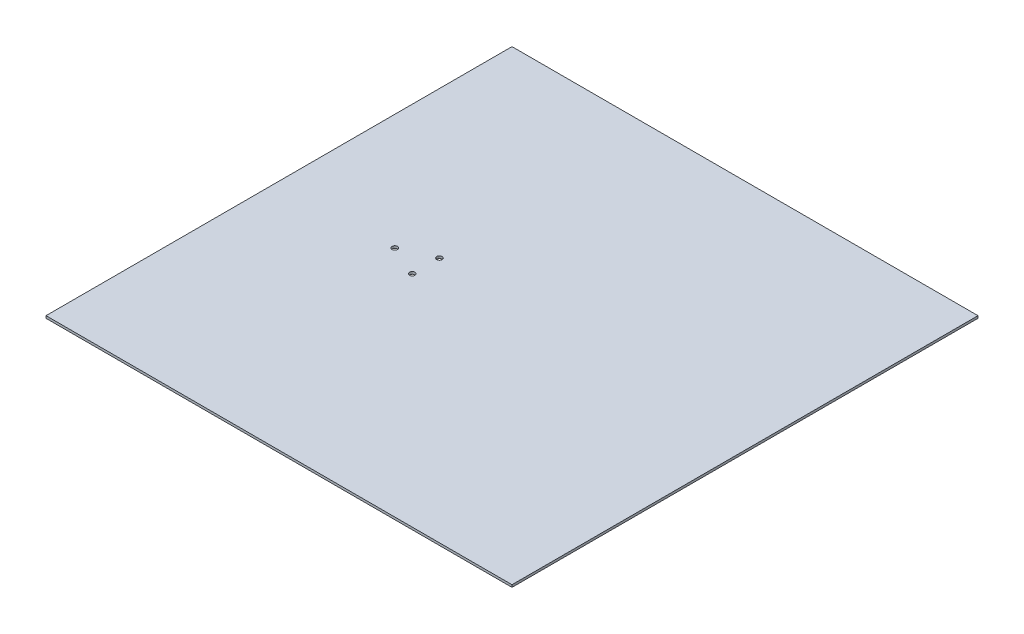
SolidWorks part; units mm, degrees
ref_plane "Front Plane" through (0, 0, 0) normal (0, 0, 1) x (1, 0, 0)
ref_plane "Top Plane" through (0, 0, 0) normal (0, 1, 0) x (1, 0, 0)
ref_plane "Right Plane" through (0, 0, 0) normal (1, 0, 0) x (0, 0, -1)
sketch "Sketch1" plane through (0, 0, 0) normal (0, 1, 0) x (1, 0, 0)
  line L1 (-300, 300) -> (300, 300)
  line L2 (-300, 300) -> (-300, -300)
  line L3 (-300, -300) -> (300, -300)
  line L4 (300, 300) -> (300, -300)
  line L5 (-300, 300) -> (300, -300) construction
  line L6 (-300, -300) -> (300, 300) construction
  point P0 (0, 0)
  dimension "D1" = 600
  dimension "D2" = 600
extrude "Boss-Extrude1" add sketch "Sketch1" along normal blind 3
sketch "Sketch2" plane through (0, 3, 0) normal (0, 1, 0) x (1, 0, 0)
  circle A0 centre (-110.9289, -17.5) radius 3.5
  circle A1 centre (-110.9289, 17.5) radius 3.5
  dimension "D1" = 7
extrude "Cut-Extrude1" cut sketch "Sketch2" against normal through all both and the other way through all
sketch "Sketch3" plane through (0, 3, 0) normal (0, 1, 0) x (1, 0, 0)
  line L0 (-150.9289, 57.7968) -> (-150.9289, -57.7968) construction
  circle A0 centre (-150.9289, 0) radius 3.55
extrude "Cut-Extrude2" cut sketch "Sketch3" against normal through all both and the other way through all
